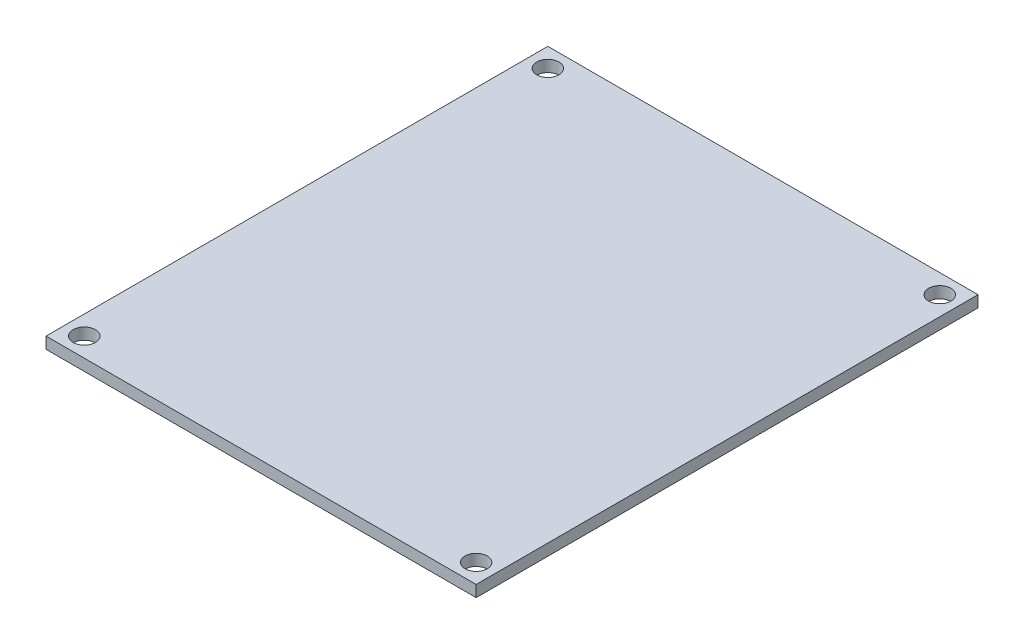
SolidWorks part; units mm, degrees
ref_plane "Přední rovina" through (0, 0, 0) normal (0, 0, 1) x (1, 0, 0)
ref_plane "Horní rovina" through (0, 0, 0) normal (0, 1, 0) x (1, 0, 0)
ref_plane "Pravá rovina" through (0, 0, 0) normal (1, 0, 0) x (0, 0, -1)
sketch "Sketch2" plane through (0, 0, 0) normal (0, 1, 0) x (1, 0, 0)
  line L1 (-30, 35) -> (30, 35)
  line L2 (-30, 35) -> (-30, -35)
  line L3 (-30, -35) -> (30, -35)
  line L4 (30, 35) -> (30, -35)
  line L5 (-30, 35) -> (30, -35) construction
  line L6 (-30, -35) -> (30, 35) construction
  point P0 (0, 0)
  dimension "D1" = 70
  dimension "D2" = 60
extrude "Boss-Extrude1" add sketch "Sketch2" along normal blind 1.6
sketch "Sketch3" plane through (0, 1.6, 0) normal (0, 1, 0) x (1, 0, 0)
  line L0 (30, 35) -> (-30, 35) construction
  line L1 (-30, 35) -> (-30, -35) construction
  line L2 (0, 0) -> (0, 35) construction
  line L3 (0, 0) -> (-30, 0) construction
  circle A0 centre (-27.333, 32.333) radius 1.55
  circle A1 centre (27.333, 32.333) radius 1.55
  circle A2 centre (27.333, -32.333) radius 1.55
  circle A3 centre (-27.333, -32.333) radius 1.55
  dimension "D1" = 3.1
  dimension "D2" = 2.667
  dimension "D3" = 2.667
extrude "Cut-Extrude1" cut sketch "Sketch3" against normal through all
